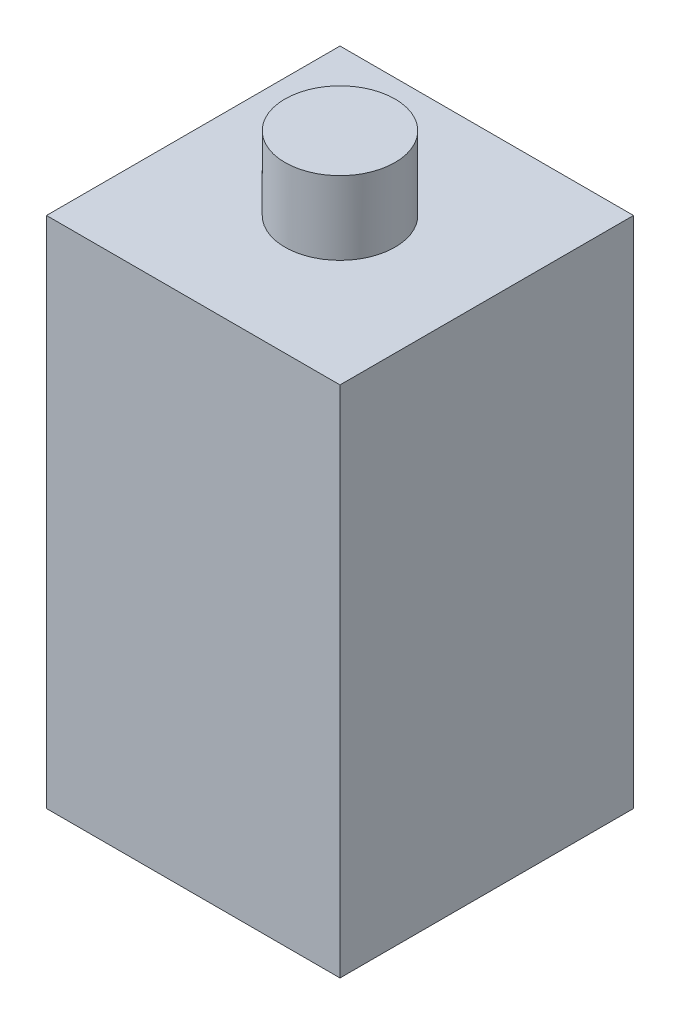
SolidWorks part; units mm, degrees
ref_plane "Front Plane" through (0, 0, 0) normal (0, 0, 1) x (1, 0, 0)
ref_plane "Top Plane" through (0, 0, 0) normal (0, 1, 0) x (1, 0, 0)
ref_plane "Right Plane" through (0, 0, 0) normal (1, 0, 0) x (0, 0, -1)
sketch "Sketch1" plane through (0, 0, 0) normal (0, 1, 0) x (1, 0, 0)
  line L1 (-10, -10) -> (10, -10)
  line L2 (-10, -10) -> (-10, 10)
  line L3 (-10, 10) -> (10, 10)
  line L4 (10, -10) -> (10, 10)
  line L5 (-10, -10) -> (10, 10) construction
  line L6 (-10, 10) -> (10, -10) construction
  point P0 (0, 0)
  dimension "D1" = 20
sketch "Sketch2" plane through (0, 0, 0) normal (0, 1, 0) x (1, 0, 0)
  circle A0 centre (0, 0) radius 3.75
  dimension "D1" = 7.5
extrude "Boss-Extrude1" add sketch "Sketch2" along normal blind 5
extrude "Boss-Extrude2" add sketch "Sketch1" against normal blind 35
